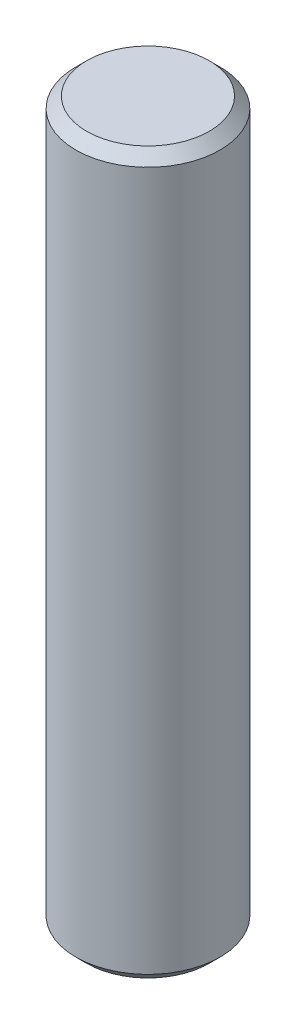
SolidWorks part; units mm, degrees
material "AISI 304"
ref_plane "前视基准面" through (0, 0, 0) normal (0, 0, 1) x (1, 0, 0)
ref_plane "上视基准面" through (0, 0, 0) normal (0, 1, 0) x (1, 0, 0)
ref_plane "右视基准面" through (0, 0, 0) normal (1, 0, 0) x (0, 0, -1)
sketch "草图1" plane through (0, 0, 0) normal (0, 1, 0) x (1, 0, 0)
  circle A0 centre (0, 0) radius 2
  dimension "D1" = 4
extrude "凸台-拉伸1" add sketch "草图1" along normal mid plane 20
chamfer "倒角1" distance 0.3 angle 45 2 edges at (0, -10, 2) (0, 10, 2)
